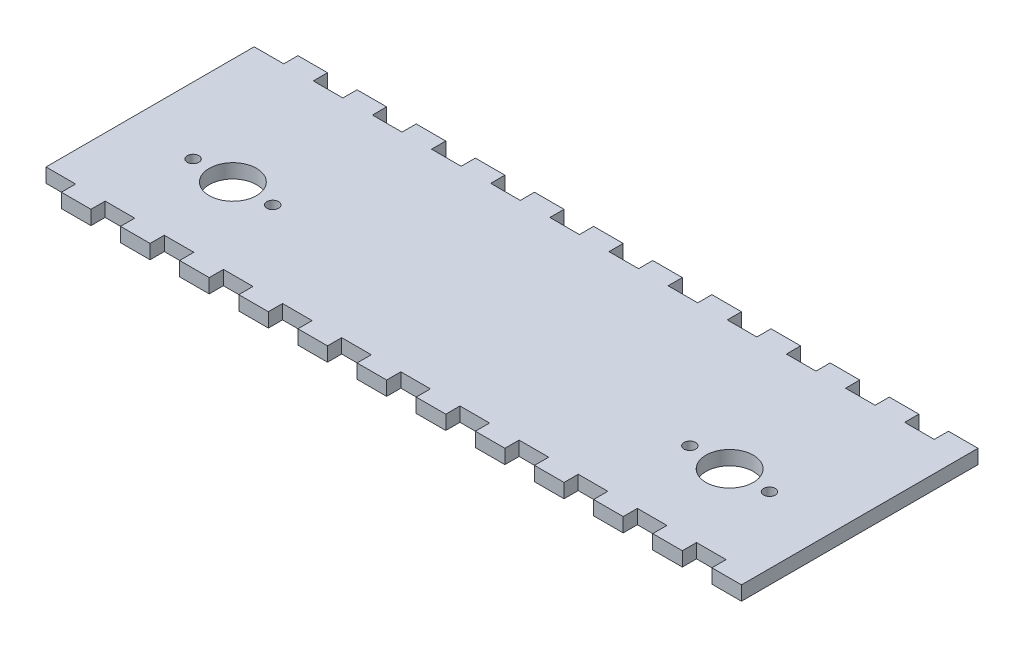
SolidWorks part; units mm, degrees
ref_plane "Front Plane" through (0, 0, 0) normal (0, 0, 1) x (1, 0, 0)
ref_plane "Top Plane" through (0, 0, 0) normal (0, 1, 0) x (1, 0, 0)
ref_plane "Right Plane" through (0, 0, 0) normal (1, 0, 0) x (0, 0, -1)
sketch "Sketch1" plane through (0, 0, 0) normal (0, 1, 0) x (1, 0, 0)
  line L1 (-76.2, -25.4) -> (76.2, -25.4)
  line L2 (-76.2, -25.4) -> (-76.2, 25.4)
  line L3 (-76.2, 25.4) -> (76.2, 25.4)
  line L4 (76.2, -25.4) -> (76.2, 25.4)
  line L5 (-76.2, -25.4) -> (76.2, 25.4) construction
  line L6 (-76.2, 25.4) -> (76.2, -25.4) construction
  point P0 (0, 0)
  dimension "D1" = 152.4
  dimension "D2" = 50.8
extrude "Boss-Extrude1" add sketch "Sketch1" along normal blind 3.048
sketch "Sketch2" plane through (0, 3.048, 0) normal (0, 1, 0) x (1, 0, 0)
  line L0 (-76.2, 22.352) -> (-69.85, 22.352)
  line L1 (-76.2, 25.4) -> (-76.2, -25.4) construction
  line L2 (-69.85, 22.352) -> (-69.85, 25.4)
  line L3 (76.2, 25.4) -> (-76.2, 25.4) construction
  line L4 (-69.85, 25.4) -> (-63.5, 25.4)
  line L5 (-76.2, 22.352) -> (-76.2, 25.4)
  line L6 (-63.5, 22.352) -> (-63.5, 25.4)
  line L7 (-63.5, 22.352) -> (-57.15, 22.352)
  line L8 (-57.15, 22.352) -> (-57.15, 25.4)
  line L9 (-57.15, 25.4) -> (-50.8, 25.4)
  line L10 (-50.8, 22.352) -> (-50.8, 25.4)
  line L11 (-50.8, 22.352) -> (-44.45, 22.352)
  line L12 (-44.45, 22.352) -> (-44.45, 25.4)
  line L13 (-44.45, 25.4) -> (-38.1, 25.4)
  line L14 (-38.1, 22.352) -> (-38.1, 25.4)
  line L15 (-38.1, 22.352) -> (-31.75, 22.352)
  line L16 (-31.75, 22.352) -> (-31.75, 25.4)
  line L17 (-31.75, 25.4) -> (-25.4, 25.4)
  line L18 (-25.4, 22.352) -> (-25.4, 25.4)
  line L19 (-25.4, 22.352) -> (-19.05, 22.352)
  line L20 (-19.05, 22.352) -> (-19.05, 25.4)
  line L21 (-19.05, 25.4) -> (-12.7, 25.4)
  line L22 (-12.7, 22.352) -> (-12.7, 25.4)
  line L23 (-12.7, 22.352) -> (-6.35, 22.352)
  line L24 (-6.35, 22.352) -> (-6.35, 25.4)
  line L25 (-6.35, 25.4) -> (0, 25.4)
  line L26 (0, 22.352) -> (0, 25.4)
  line L27 (0, 22.352) -> (6.35, 22.352)
  line L28 (6.35, 22.352) -> (6.35, 25.4)
  line L29 (6.35, 25.4) -> (12.7, 25.4)
  line L30 (12.7, 22.352) -> (12.7, 25.4)
  line L31 (12.7, 22.352) -> (19.05, 22.352)
  line L32 (19.05, 22.352) -> (19.05, 25.4)
  line L33 (19.05, 25.4) -> (25.4, 25.4)
  line L34 (25.4, 22.352) -> (25.4, 25.4)
  line L35 (25.4, 22.352) -> (31.75, 22.352)
  line L36 (31.75, 22.352) -> (31.75, 25.4)
  line L37 (31.75, 25.4) -> (38.1, 25.4)
  line L38 (38.1, 22.352) -> (38.1, 25.4)
  line L39 (38.1, 22.352) -> (44.45, 22.352)
  line L40 (44.45, 22.352) -> (44.45, 25.4)
  line L41 (44.45, 25.4) -> (50.8, 25.4)
  line L42 (50.8, 22.352) -> (50.8, 25.4)
  line L43 (50.8, 22.352) -> (57.15, 22.352)
  line L44 (57.15, 22.352) -> (57.15, 25.4)
  line L45 (57.15, 25.4) -> (63.5, 25.4)
  line L46 (63.5, 22.352) -> (63.5, 25.4)
  line L47 (63.5, 22.352) -> (69.85, 22.352)
  line L48 (69.85, 22.352) -> (69.85, 25.4)
  line L49 (69.85, 25.4) -> (76.2, 25.4)
  line L50 (-76.2, 25.4) -> (76.2, 25.4)
  line L51 (-76.2, 0) -> (76.2, 0) construction
  line L52 (76.2, -25.4) -> (76.2, 25.4) construction
  line L53 (-76.2, -25.4) -> (76.2, -25.4)
  line L54 (69.85, -25.4) -> (76.2, -25.4)
  line L55 (69.85, -22.352) -> (69.85, -25.4)
  line L56 (63.5, -22.352) -> (69.85, -22.352)
  line L57 (63.5, -22.352) -> (63.5, -25.4)
  line L58 (57.15, -25.4) -> (63.5, -25.4)
  line L59 (57.15, -22.352) -> (57.15, -25.4)
  line L60 (50.8, -22.352) -> (57.15, -22.352)
  line L61 (50.8, -22.352) -> (50.8, -25.4)
  line L62 (44.45, -25.4) -> (50.8, -25.4)
  line L63 (44.45, -22.352) -> (44.45, -25.4)
  line L64 (38.1, -22.352) -> (44.45, -22.352)
  line L65 (38.1, -22.352) -> (38.1, -25.4)
  line L66 (31.75, -25.4) -> (38.1, -25.4)
  line L67 (31.75, -22.352) -> (31.75, -25.4)
  line L68 (25.4, -22.352) -> (31.75, -22.352)
  line L69 (25.4, -22.352) -> (25.4, -25.4)
  line L70 (19.05, -25.4) -> (25.4, -25.4)
  line L71 (19.05, -22.352) -> (19.05, -25.4)
  line L72 (12.7, -22.352) -> (19.05, -22.352)
  line L73 (12.7, -22.352) -> (12.7, -25.4)
  line L74 (6.35, -25.4) -> (12.7, -25.4)
  line L75 (6.35, -22.352) -> (6.35, -25.4)
  line L76 (0, -22.352) -> (6.35, -22.352)
  line L77 (0, -22.352) -> (0, -25.4)
  line L78 (-6.35, -25.4) -> (0, -25.4)
  line L79 (-6.35, -22.352) -> (-6.35, -25.4)
  line L80 (-12.7, -22.352) -> (-6.35, -22.352)
  line L81 (-12.7, -22.352) -> (-12.7, -25.4)
  line L82 (-19.05, -25.4) -> (-12.7, -25.4)
  line L83 (-19.05, -22.352) -> (-19.05, -25.4)
  line L84 (-25.4, -22.352) -> (-19.05, -22.352)
  line L85 (-25.4, -22.352) -> (-25.4, -25.4)
  line L86 (-31.75, -25.4) -> (-25.4, -25.4)
  line L87 (-31.75, -22.352) -> (-31.75, -25.4)
  line L88 (-38.1, -22.352) -> (-31.75, -22.352)
  line L89 (-38.1, -22.352) -> (-38.1, -25.4)
  line L90 (-44.45, -25.4) -> (-38.1, -25.4)
  line L91 (-44.45, -22.352) -> (-44.45, -25.4)
  line L92 (-50.8, -22.352) -> (-44.45, -22.352)
  line L93 (-50.8, -22.352) -> (-50.8, -25.4)
  line L94 (-57.15, -25.4) -> (-50.8, -25.4)
  line L95 (-57.15, -22.352) -> (-57.15, -25.4)
  line L96 (-63.5, -22.352) -> (-57.15, -22.352)
  line L97 (-63.5, -22.352) -> (-63.5, -25.4)
  line L98 (-76.2, -22.352) -> (-76.2, -25.4)
  line L99 (-69.85, -25.4) -> (-63.5, -25.4)
  line L100 (-69.85, -22.352) -> (-69.85, -25.4)
  line L101 (-76.2, -22.352) -> (-69.85, -22.352)
  line M5 (76.2, 25.4) -> (-76.2, 25.4)
  line M6 (-76.2, 25.4) -> (-76.2, -25.4)
  line M7 (-76.2, -25.4) -> (76.2, -25.4)
  dimension "D1" = 3.048
  dimension "D2" = 6.35
  dimension "D3" = 6.35
  dimension "D4" = 12
extrude "Cut-Extrude1" cut sketch "Sketch2" against normal through all contours L0 L2 M5 M6 | L7 L8 L6 M5 | L11 L12 L10 M5 | L15 L16 L14 M5 | L19 L20 L18 M5 | L23 L24 L22 M5 | L31 L32 L30 M5 | L27 L28 L26 M5 | L35 L36 L34 M5 | L39 L40 L38 M5 | L43 L44 L42 M5 | L47 L48 L46 M5 | L101 L100 M6 M7 | L96 L97 L53 L95 | L92 L93 L53 L91 | L88 L89 L53 L87 | L84 L85 L53 L83 | L80 L81 L53 L79 | L76 L77 L53 L75 | L72 L73 L53 L71 | L68 L69 L53 L67 | L64 L65 L53 L63 | L60 L61 L53 L59 | L56 L57 L53 L55
sketch "Sketch4" plane through (0, 3.048, 0) normal (0, 1, 0) x (1, 0, 0)
  line L0 (76.2, 18.9225) -> (-76.2, 18.9225) construction
  line L1 (76.2, -25.4) -> (76.2, 25.4) construction
  line L2 (-76.2, 22.352) -> (-76.2, -22.352) construction
  line L3 (0, 18.9225) -> (0, -19.2478) construction
  line L4 (-61.89, -5.08) -> (-44.79, -5.08) construction
  line L5 (-57.15, -25.4) -> (-50.8, -25.4) construction
  circle A0 centre (-61.89, -5.08) radius 1.25
  circle A1 centre (-44.79, -5.08) radius 1.25
  circle A2 centre (-53.34, -5.08) radius 5.08
  circle A3 centre (44.79, -5.08) radius 1.25
  circle A4 centre (53.34, -5.08) radius 5.08
  circle A5 centre (61.89, -5.08) radius 1.25
  dimension "D1" = 17.1
  dimension "D2" = 2.5
  dimension "D3" = 2.5
  dimension "D4" = 10.16
  dimension "D5" = 22.86
  dimension "D6" = 20.32
extrude "Cut-Extrude2" cut sketch "Sketch4" against normal through all
